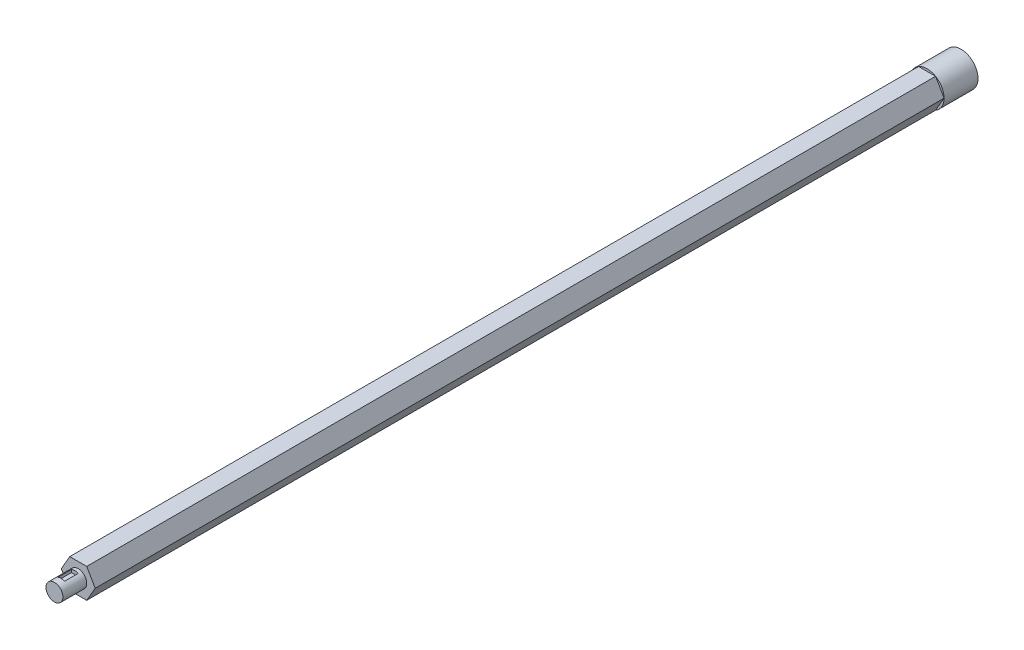
SolidWorks part; units mm, degrees
ref_plane "前视基准面" through (0, 0, 0) normal (0, 0, 1) x (1, 0, 0)
ref_plane "上视基准面" through (0, 0, 0) normal (0, 1, 0) x (1, 0, 0)
ref_plane "右视基准面" through (0, 0, 0) normal (1, 0, 0) x (0, 0, -1)
sketch "草图1" plane through (0, 0, 0) normal (0, 0, 1) x (1, 0, 0)
  line L7 (5, 0) -> (2.5, 4.3301)
  line L8 (2.5, 4.3301) -> (-2.5, 4.3301)
  line L9 (-2.5, 4.3301) -> (-5, 0)
  line L10 (-5, 0) -> (-2.5, -4.3301)
  line L11 (-2.5, -4.3301) -> (2.5, -4.3301)
  line L12 (2.5, -4.3301) -> (5, 0)
  circle A0 centre (0, 0) radius 5 construction
  dimension "D1" = 10
extrude "凸台-拉伸1" add sketch "草图1" along normal blind 250
sketch "草图2" plane through (0, 0, 250) normal (0, 0, 1) x (1, 0, 0)
  circle A0 centre (0, 0) radius 2.5
  dimension "D1" = 5
extrude "凸台-拉伸2" add sketch "草图2" along normal blind 10
sketch "草图3" plane through (0, 0, 0) normal (0, 0, -1) x (-1, 0, 0)
  circle A0 centre (0, 0) radius 5
  dimension "D1" = 10
extrude "凸台-拉伸3" add sketch "草图3" along normal blind 10
sketch "草图4" plane through (0, 0, 260) normal (0, 0, 1) x (1, 0, 0)
  line L0 (0, 5.3594) -> (0, -5.4971) construction
  line L2 (-1, 3.3356) -> (1, 3.3356)
  line L3 (-1, 3.3356) -> (-1, 1.5)
  line L4 (-1, 1.5) -> (1, 1.5)
  line L5 (1, 3.3356) -> (1, 1.5)
  dimension "D1" = 2
  dimension "D2" = 1
  dimension "D3" = 1.5
extrude "切除-拉伸1" cut sketch "草图4" against normal blind 10
sketch "草图6" plane through (0, 0, 260) normal (0, 0, 1) x (1, 0, 0)
  circle A0 centre (0, 0) radius 2.5
extrude "凸台-拉伸5" add sketch "草图6" against normal blind 5
sketch "草图9" plane through (0, 0, -10) normal (0, 0, -1) x (-1, 0, 0)
  circle A0 centre (0, 0) radius 2.5
extrude "凸台-拉伸7" add sketch "草图9" against normal blind 5
sketch "草图10" plane through (0, 0, -10) normal (0, 0, -1) x (-1, 0, 0)
  circle A0 centre (0, 0) radius 2.5
extrude "切除-拉伸3" cut sketch "草图10" against normal blind 3
sketch "草图11" plane through (0, 0, 260) normal (0, 0, 1) x (1, 0, 0)
  circle A0 centre (0, 0) radius 2.5
extrude "切除-拉伸4" cut sketch "草图11" against normal blind 3
sketch "草图12" plane through (0, 0, -10) normal (0, 0, -1) x (-1, 0, 0)
  circle A0 centre (0, 0) radius 5
extrude "凸台-拉伸8" add sketch "草图12" against normal blind 10
sketch "草图14" plane through (0, 0, 250) normal (0, 0, 1) x (1, 0, 0)
  circle A0 centre (0, 0) radius 2.5
extrude "凸台-拉伸10" add sketch "草图14" along normal blind 1
